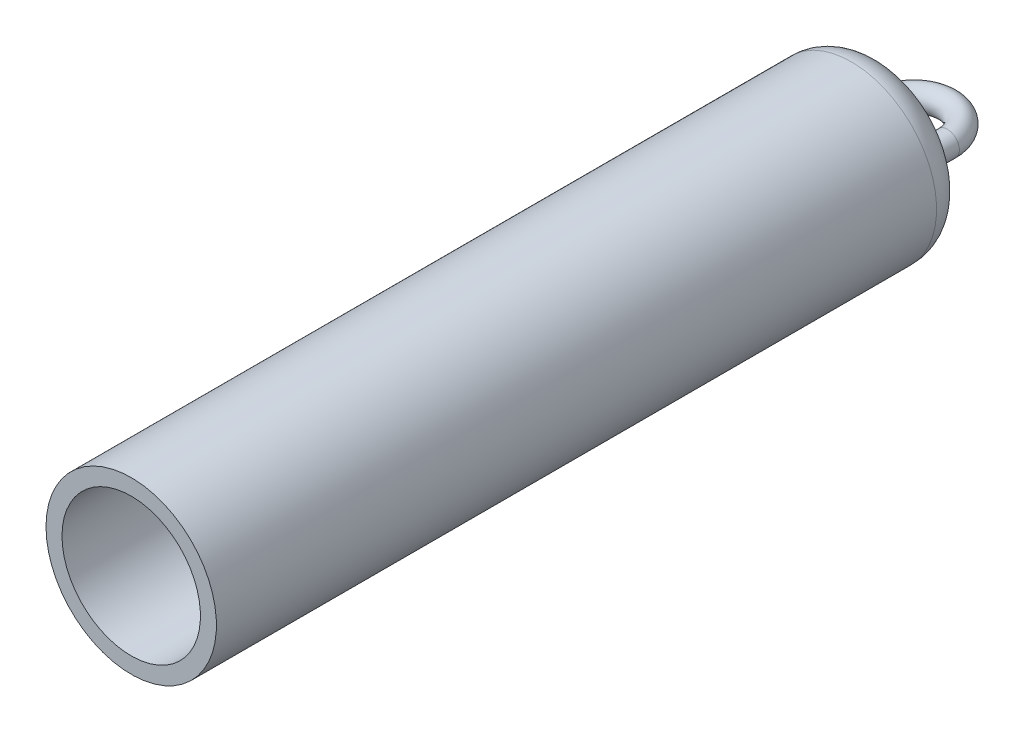
SolidWorks part; units mm, degrees
ref_plane "Plan de face" through (0, 0, 0) normal (0, 0, 1) x (1, 0, 0)
ref_plane "Plan de dessus" through (0, 0, 0) normal (0, 1, 0) x (1, 0, 0)
ref_plane "Plan de droite" through (0, 0, 0) normal (1, 0, 0) x (0, 0, -1)
sketch "Esquisse2" plane through (0, 0, 0) normal (0, 0, 1) x (1, 0, 0)
  circle A0 centre (0, 0) radius 8.65
  circle A1 centre (0, 0) radius 10.65
  dimension "D1" = 21.3
  dimension "D2" = 2
extrude "Boss.-Extru.1" add sketch "Esquisse2" along normal mid plane 90
sketch "Esquisse3" plane through (0, 0, 0) normal (0, 1, 0) x (1, 0, 0)
  line L0 (-6.65, 49) -> (0, 49)
  line L1 (-10.65, 45) -> (-10.65, -45) construction
  line L2 (0, 49) -> (0, 45)
  line L3 (8.65, 45) -> (-8.65, 45) construction
  line L4 (0, 45) -> (-10.65, 45)
  arc A0 (-10.65, 45) -> (-6.65, 49) centre (-6.65, 45) cw
  dimension "D1" = 4
revolve "Révolution1" add sketch "Esquisse3" angle 360 about L2
sketch "Esquisse4" plane through (0, 0, -45) normal (0, 0, 1) x (1, 0, 0)
  line L0 (0, -11.715) -> (0, 11.715) construction
  circle A0 centre (-4.15, 0) radius 1.5
  circle A2 centre (0, 0) radius 8.65 construction
  circle A3 centre (0, 0) radius 8.65 construction
  circle A4 centre (4.15, 0) radius 1.5
  point P10 (-8.65, 0)
  dimension "D1" = 3
  dimension "D3" = 4.5
sketch "Esquisse5" plane through (0, 0, 0) normal (1, 0, 0) x (0, 0, -1)
  line L0 (49, -6.65) -> (49, 6.65) construction
  circle A0 centre (57, 0) radius 1.5
  dimension "D1" = 3
  dimension "D2" = 8
sketch "Esquisse6" plane through (0, 0, 0) normal (0, 1, 0) x (1, 0, 0)
  line L0 (-2.65, 45) -> (-2.65, 52.85)
  line L2 (2.65, 52.85) -> (2.65, 45)
  line L5 (0, 55.5) -> (0, 58.5) construction
  arc A0 (-2.65, 52.85) -> (2.65, 52.85) centre (0, 52.85) cw
  point P4 (0, 55.5)
  point P8 (-2.65, 45)
sweep "Balayage3" add profiles "Esquisse5" path "Esquisse6"
